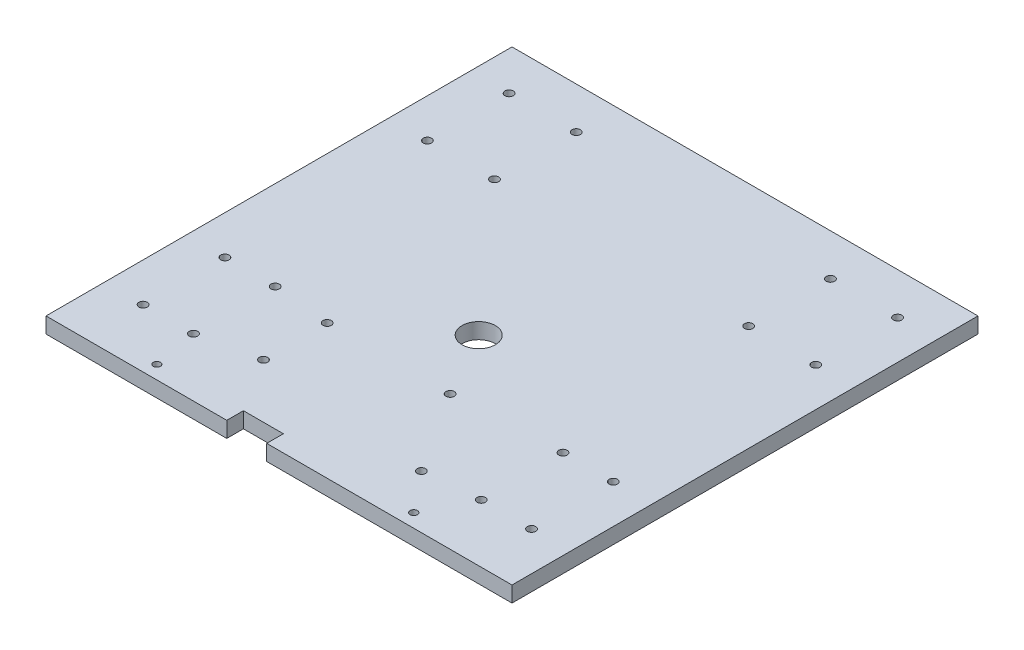
SolidWorks part; units mm, degrees
ref_plane "Front Plane" through (0, 0, 0) normal (0, 0, 1) x (1, 0, 0)
ref_plane "Top Plane" through (0, 0, 0) normal (0, 1, 0) x (1, 0, 0)
ref_plane "Right Plane" through (0, 0, 0) normal (1, 0, 0) x (0, 0, -1)
sketch "Sketch1" plane through (0, 0, 0) normal (0, 1, 0) x (1, 0, 0)
  line L1 (0, 0) -> (177.8, 0)
  line L2 (0, 0) -> (0, 177.8)
  line L3 (0, 177.8) -> (177.8, 177.8)
  line L4 (177.8, 0) -> (177.8, 177.8)
  dimension "D1" = 177.8
  dimension "D2" = 177.8
extrude "Boss-Extrude1" add sketch "Sketch1" along normal blind 5.9944
sketch "Sketch5" plane through (0, 0, 0) normal (0, -1, 0) x (1, 0, 0)
  circle A0 centre (163, -22.25) radius 1.6
  circle A1 centre (163, -53.45) radius 1.6
  circle A2 centre (143.8, -22.25) radius 1.6
  circle A3 centre (143.8, -53.45) radius 1.6
  circle A4 centre (14.8, -22.25) radius 1.6
  circle A5 centre (14.8, -53.45) radius 1.6
  circle A8 centre (40.4, -130.7) radius 1.6
  circle A9 centre (14.8, -130.7) radius 1.6
  circle A10 centre (14.8, -161.9) radius 1.6
  circle A11 centre (40.4, -161.9) radius 1.6
  circle A12 centre (163, -130.7) radius 1.6
  circle A13 centre (163, -161.9) radius 1.6
  circle A14 centre (137.4, -130.7) radius 1.6
  circle A15 centre (137.4, -161.9) radius 1.6
  circle A16 centre (34, -22.25) radius 1.6
  circle A17 centre (34, -53.45) radius 1.6
extrude "Cut-Extrude1" cut sketch "Sketch5" against normal up to surface (5.9944 mm away) and the other way through all up to face at (88.9, 5.9944, -88.9)
sketch "Sketch6" plane through (0, 5.9944, 0) normal (0, 1, 0) x (1, 0, 0)
  line L2 (68.9736, 0) -> (74.1006, 0)
  line L3 (0, 0) -> (177.8, 0) construction
  line L5 (68.9736, 0) -> (84.2136, 0)
  line L6 (68.9736, 0) -> (68.9736, 6.35)
  line L7 (68.9736, 6.35) -> (84.2136, 6.35)
  line L8 (84.2136, 0) -> (84.2136, 6.35)
  dimension "D1" = 6.35
  dimension "D2" = 15.24
extrude "Cut-Extrude2" cut sketch "Sketch6" against normal through all both
sketch "Sketch7" plane through (0, 5.9944, 0) normal (0, 1, 0) x (1, 0, 0)
  circle A0 centre (102.855, 51.32) radius 1.6
  circle A1 centre (55.9736, 51.32) radius 1.6
  circle A2 centre (55.9736, 27) radius 1.6
  circle A3 centre (122.855, 20.35) radius 1.6
extrude "Cut-Extrude3" cut sketch "Sketch7" against normal through all both contours A1 | A0 | A3 | A2
sketch "Sketch8" plane through (0, 5.9944, 0) normal (0, 1, 0) x (1, 0, 0)
  line L0 (177.8, 0) -> (177.8, 177.8) construction
  line L1 (177.8, 177.8) -> (0, 177.8) construction
  circle A0 centre (88.9, 76.2) radius 6.35
  dimension "D1" = 12.7
  dimension "D2" = 88.9
  dimension "D3" = 101.6
extrude "Cut-Extrude4" cut sketch "Sketch8" against normal through all both
sketch "Sketch9" plane through (0, 0, 0) normal (0, -1, 0) x (-1, 0, 0)
  circle A0 centre (-37.15, 5.16) radius 1.3633
  circle A1 centre (-135.15, 5.16) radius 1.3861
extrude "Cut-Extrude5" cut sketch "Sketch9" against normal through all both
